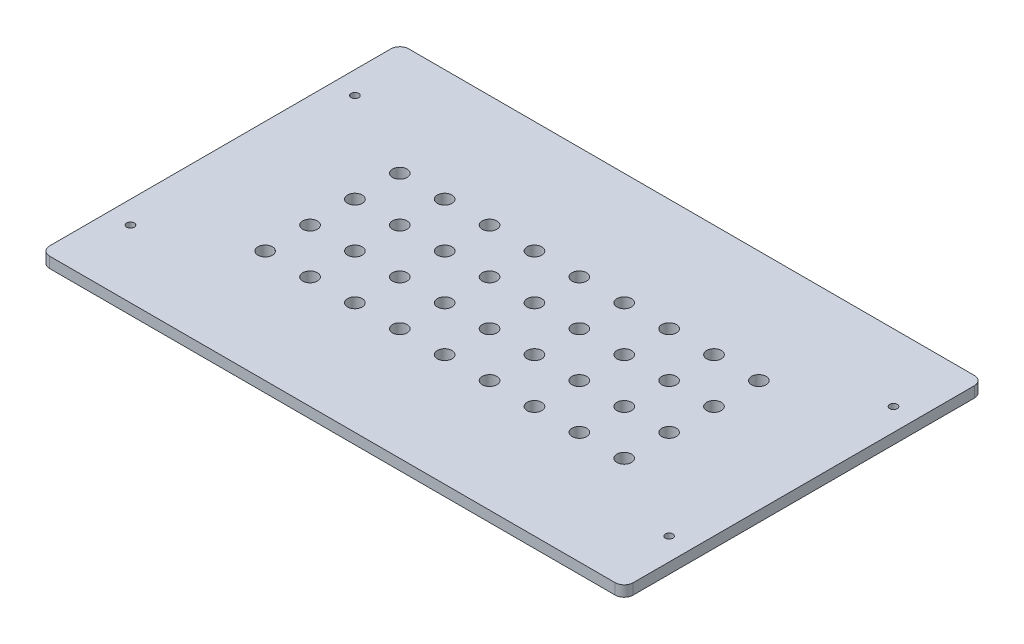
SolidWorks part; units mm, degrees
material "1060 Alloy"
ref_plane "Front Plane" through (0, 0, 0) normal (0, 0, 1) x (1, 0, 0)
ref_plane "Top Plane" through (0, 0, 0) normal (0, 1, 0) x (1, 0, 0)
ref_plane "Right Plane" through (0, 0, 0) normal (1, 0, 0) x (0, 0, -1)
sketch "Sketch1" plane through (0, 0, 0) normal (0, 1, 0) x (1, 0, 0)
  line L1 (0, 0) -> (650, 0)
  line L2 (0, 0) -> (0, -400)
  line L3 (0, -400) -> (650, -400)
  line L4 (650, 0) -> (650, -400)
  dimension "D1" = 400
  dimension "D2" = 650
extrude "Boss-Extrude1" add sketch "Sketch1" along normal blind 12
fillet "Fillet1" radius 10 4 edges at (0, 6, 0) (650, 6, 0) (650, 6, 400) (0, 6, 400)
sketch "Sketch11" plane through (0, 12, 0) normal (0, 1, 0) x (1, 0, 0)
  line L0 (10, 0) -> (10, -400) construction
  line L1 (640, 0) -> (640, -400) construction
  line L2 (10, 0) -> (10, -20) construction
  line L3 (10, -20) -> (640, -20) construction
  line L4 (325, -20) -> (325, 0) construction
  line L5 (640, 0) -> (10, 0) construction
  line L6 (10, -10) -> (640, -10) construction
  line L7 (55, -10) -> (10, -10) construction
  line L8 (566.1661, -10) -> (640, -10) construction
  circle A0 centre (55, -10) radius 2
  ellipse E0 centre (566.1661, -10) end of major axis (595, -10) minor radius 3
  point P23 (325, -10)
  dimension "D2" = 45
  dimension "D4" = 73.8339
  dimension "D1" = 20
  dimension "D3" = 45
sketch "Sketch24" plane through (0, 0, 0) normal (0, -1, 0) x (-1, 0, 0)
  line L0 (-10, 0) -> (-10, -20) construction
  line L5 (-500, -20) -> (-500, 0) construction
  line L6 (-640, 0) -> (-10, 0) construction
  line L7 (-150, -20) -> (-150, 0) construction
  line L9 (-640, 0) -> (-640, -20) construction
  line L11 (-640, -10) -> (-10, -10) construction
  point P17 (-500, -10)
  point P19 (-150, -10)
  dimension "D1" = 140
  dimension "D2" = 140
  dimension "D3" = 630
  dimension "D4" = 20
  dimension "D5" = 140
sketch "Sketch31" plane through (0, 12, 0) normal (0, 1, 0) x (1, 0, 0)
  line L0 (0, -200) -> (100, -200) construction
  line L1 (0, -10) -> (0, -390) construction
  line L2 (100, -400) -> (100, -300) construction
  line L3 (10, -400) -> (640, -400) construction
  line L4 (650, -200) -> (550, -200) construction
  line L5 (650, -390) -> (650, -10) construction
  line L6 (550, 0) -> (550, -100)
  line L7 (640, 0) -> (10, 0) construction
  line L8 (125, -250) -> (125, -300) construction
  line L13 (100, -300) -> (150, -300)
  line L14 (100, -300) -> (100, -250)
  line L15 (100, -250) -> (150, -250)
  line L16 (150, -300) -> (150, -250)
  circle A0 centre (125, -275) radius 8.15
  dimension "D5" = 100
  dimension "D6" = 16.3
  dimension "D1" = 100
  dimension "D2" = 100
  dimension "D3" = 50
  dimension "D4" = 50
extrude "Cut-Extrude3" cut sketch "Sketch31" against normal through all contours A0
pattern_linear "LPattern1" count 9 spacing 50 along (1, 0, 0) of "Cut-Extrude3"
pattern_linear "LPattern2" count 4 spacing 50 along (0, 0, -1) of "LPattern1", "Cut-Extrude3"
sketch "Sketch32" plane through (0, 0, 0) normal (0, -1, 0) x (-1, 0, 0)
  line L0 (-50, 0) -> (-50, -50) construction
  line L1 (-640, 0) -> (-10, 0) construction
  line L2 (0, -10) -> (0, -390) construction
  line L3 (-50, -50) -> (0, -50)
  line L4 (-50, -50) -> (-50, -100)
  line L5 (-50, -100) -> (0, -100)
  line L6 (0, -50) -> (0, -100)
  line L7 (-25, -100) -> (-25, -50) construction
  line L16 (-50, -75) -> (0, -75) construction
  point P15 (-25, -75)
  dimension "D1" = 50
  dimension "D2" = 50
  dimension "D3" = 50
  dimension "D4" = 50
hole_wizard "M8 Clearance Hole2" positions "Sketch32" profile "Sketch33" hole size "M8" standard "DIN" end condition through all
sketch "Sketch33" plane through (25, 0, 75) normal (1, 0, 0) x (0, 0, -1)
  line L0 (0, 0) -> (0, 12)
  line L1 (0, 12) -> (4.2, 12)
  line L2 (4.2, 12) -> (4.2, 0)
  line L5 (4.2, 0) -> (0, 0)
  line L11 (0, -6.35) -> (0, 107.95) construction
  dimension "Thru Hole Dia." = 8.4
  dimension "Thru Hole Depth" = 12
pattern_linear "LPattern3" count 2 spacing 250 along (0, 0, 1) count 2 spacing 600 along (1, 0, 0) of "M8 Clearance Hole2"
